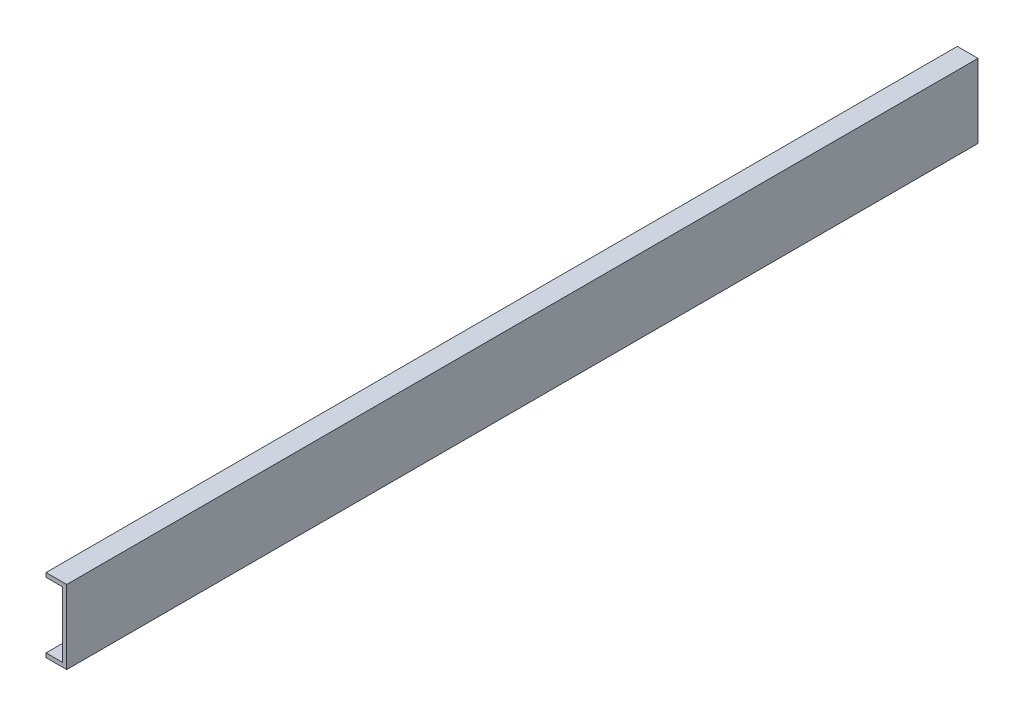
SolidWorks part; units mm, degrees
material "Galvanized Steel"
ref_plane "Front Plane" through (0, 0, 0) normal (0, 0, 1) x (1, 0, 0)
ref_plane "Top Plane" through (0, 0, 0) normal (0, 1, 0) x (1, 0, 0)
ref_plane "Right Plane" through (0, 0, 0) normal (1, 0, 0) x (0, 0, -1)
sketch "Sketch1" plane through (0, 0, 0) normal (0, 0, 1) x (1, 0, 0)
  line L1 (-6.35, -22.606) -> (6.35, -22.606)
  line L2 (-6.35, -22.606) -> (-6.35, 22.606)
  line L3 (-6.35, 22.606) -> (6.35, 22.606)
  line L4 (6.35, -22.606) -> (6.35, 22.606)
  line L5 (-6.35, -22.606) -> (6.35, 22.606) construction
  line L6 (-6.35, 22.606) -> (6.35, -22.606) construction
  point P0 (0, 0)
  dimension "D1" = 45.212
  dimension "D2" = 12.7
extrude "Boss-Extrude1" add sketch "Sketch1" along normal blind 558.8
sketch "Sketch2" plane through (0, 0, 558.8) normal (0, 0, 1) x (1, 0, 0)
  line L0 (-6.35, 22.606) -> (-6.35, -22.606) construction
  line L1 (-6.35, 20.066) -> (3.81, 20.066)
  line L2 (-6.35, 20.066) -> (-6.35, -20.066)
  line L3 (-6.35, -20.066) -> (3.81, -20.066)
  line L4 (3.81, 20.066) -> (3.81, -20.066)
  line L5 (6.35, 22.606) -> (-6.35, 22.606) construction
  line L6 (6.35, -22.606) -> (6.35, 22.606) construction
  line L7 (-6.35, -22.606) -> (6.35, -22.606) construction
  dimension "D1" = 2.54
  dimension "D2" = 2.54
  dimension "D3" = 2.54
extrude "Cut-Extrude1" cut sketch "Sketch2" against normal through all
